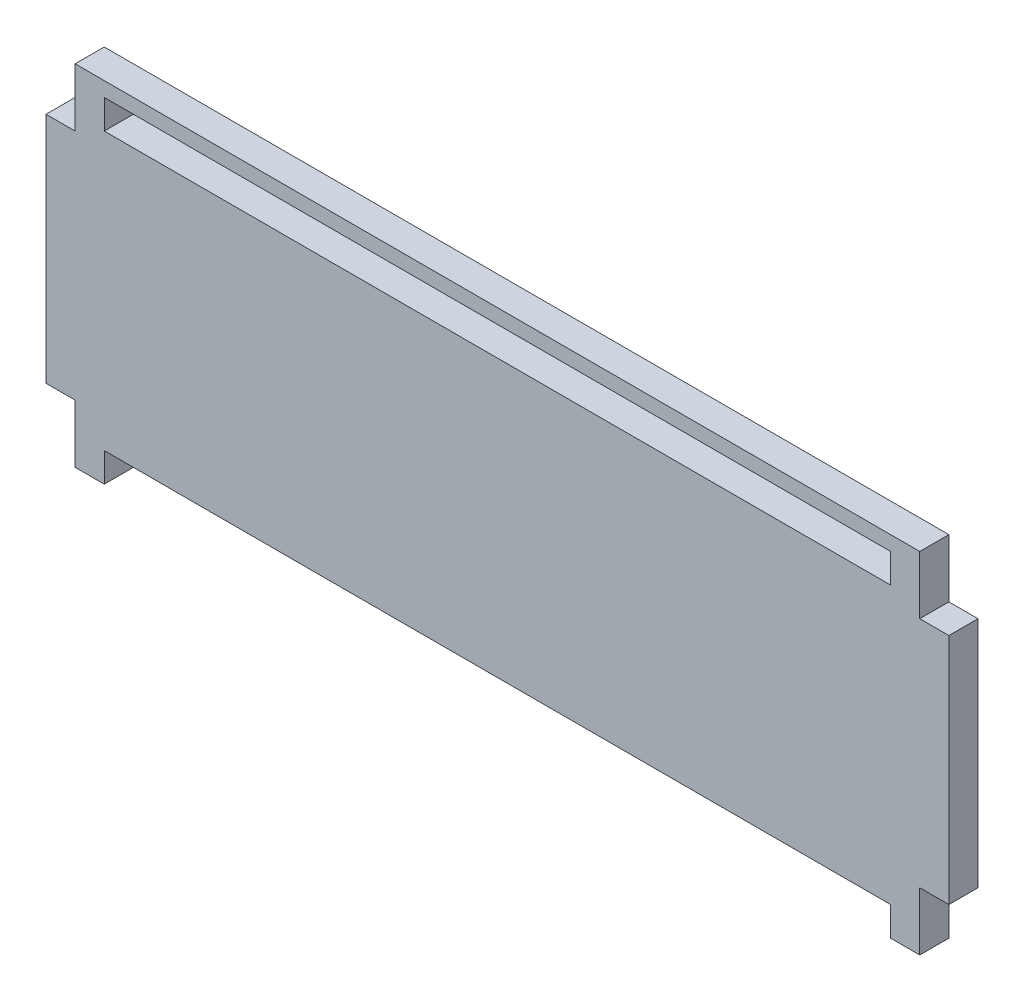
SolidWorks part; units mm, degrees
ref_plane "Front Plane" through (0, 0, 0) normal (0, 0, 1) x (1, 0, 0)
ref_plane "Top Plane" through (0, 0, 0) normal (0, 1, 0) x (1, 0, 0)
ref_plane "Right Plane" through (0, 0, 0) normal (1, 0, 0) x (0, 0, -1)
sketch "Sketch1" plane through (0, 0, 0) normal (0, 0, 1) x (1, 0, 0)
  line L0 (-82.55, -25.4) -> (-82.55, 25.4) construction
  line L1 (114.3, 38.1) -> (-82.55, 38.1)
  line L2 (114.3, 38.1) -> (114.3, -38.1)
  line L3 (114.3, -38.1) -> (-82.55, -38.1)
  line L4 (-82.55, 38.1) -> (-82.55, -38.1)
  line L5 (107.95, -38.1) -> (114.3, -38.1) construction
extrude "Boss-Extrude1" add sketch "Sketch1" along normal blind 6.35
sketch "Sketch2" plane through (0, 0, 6.35) normal (0, 0, 1) x (1, 0, 0)
  line L0 (-76.2, 25.4) -> (-76.2, 38.1) construction
  line L1 (-82.55, 38.1) -> (-76.2, 38.1)
  line L2 (-82.55, 38.1) -> (-82.55, 25.4)
  line L3 (-82.55, 25.4) -> (-76.2, 25.4)
  line L4 (-76.2, 38.1) -> (-76.2, 25.4)
  line L6 (-82.55, -38.1) -> (-76.2, -38.1)
  line L7 (-82.55, -38.1) -> (-82.55, -25.4)
  line L8 (-82.55, -25.4) -> (-76.2, -25.4)
  line L9 (-76.2, -38.1) -> (-76.2, -25.4)
  line L10 (114.3, 38.1) -> (107.95, 38.1)
  line L11 (114.3, 38.1) -> (114.3, 25.4)
  line L12 (114.3, 25.4) -> (107.95, 25.4)
  line L13 (101.6, 34.925) -> (-69.85, 34.925)
  line L14 (-69.85, 34.925) -> (-69.85, 28.575)
  line L15 (-69.85, 28.575) -> (101.6, 28.575)
  line L16 (101.6, 28.575) -> (101.6, 34.925)
  line L17 (101.6, 34.925) -> (-69.85, 34.925)
  line L18 (-69.85, 34.925) -> (-69.85, 28.575)
  line L19 (-69.85, 28.575) -> (101.6, 28.575)
  line L20 (101.6, 28.575) -> (101.6, 34.925)
  line L21 (107.95, 38.1) -> (107.95, 25.4)
  line L22 (114.3, -38.1) -> (107.95, -38.1)
  line L23 (114.3, -38.1) -> (114.3, -25.4)
  line L24 (114.3, -25.4) -> (107.95, -25.4)
  line L25 (107.95, -38.1) -> (107.95, -25.4)
  line L45 (-82.55, -38.1) -> (114.3, -38.1) construction
  line L46 (-69.85, -31.75) -> (101.6, -31.75)
  line L47 (-69.85, -31.75) -> (-69.85, -38.1)
  line L48 (-69.85, -38.1) -> (101.6, -38.1)
  line L49 (101.6, -31.75) -> (101.6, -38.1)
  line L50 (101.6, -31.75) -> (101.6, -38.1) construction
  dimension "D1" = 12.7
  dimension "D2" = 0
extrude "Cut-Extrude1" cut sketch "Sketch2" against normal through all
